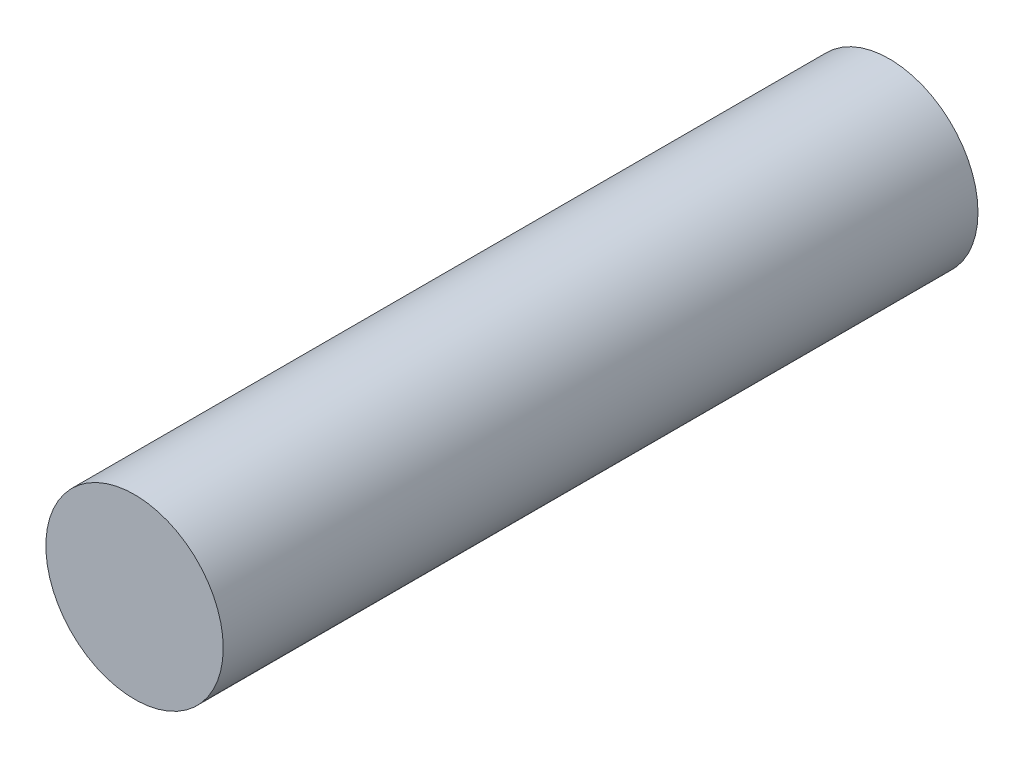
SolidWorks part; units mm, degrees
ref_plane "Front Plane" through (0, 0, 0) normal (0, 0, 1) x (1, 0, 0)
ref_plane "Top Plane" through (0, 0, 0) normal (0, 1, 0) x (1, 0, 0)
ref_plane "Right Plane" through (0, 0, 0) normal (1, 0, 0) x (0, 0, -1)
sketch "Sketch1" plane through (0, 0, 0) normal (0, 0, 1) x (1, 0, 0)
  circle A0 centre (0, 0) radius 2.35
  dimension "D1" = 4.7
extrude "Boss-Extrude1" add sketch "Sketch1" along normal blind 20
